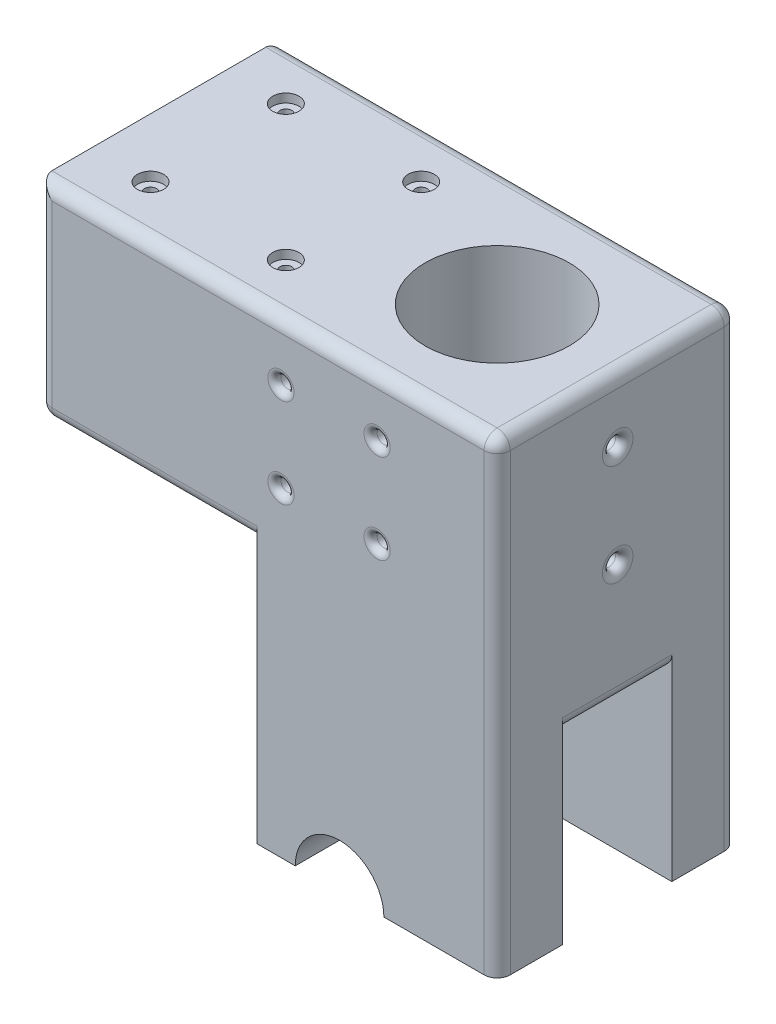
SolidWorks part; units mm, degrees
ref_plane "Front Plane" through (0, 0, 0) normal (1, 0, 0) x (0, 1, 0)
ref_plane "Top Plane" through (0, 0, 0) normal (0, 0, 1) x (0, 1, 0)
ref_plane "Right Plane" through (0, 0, 0) normal (0, 1, 0) x (-1, 0, 0)
sketch "Sketch1" plane through (0, 0, 0) normal (0, 0, 1) x (0, 1, 0)
  line L1 (-32.5, 27.5) -> (32.5, 27.5)
  line L2 (-32.5, 27.5) -> (-32.5, -27.5)
  line L3 (-32.5, -27.5) -> (32.5, -27.5)
  line L4 (32.5, 27.5) -> (32.5, -27.5)
  line L5 (-32.5, 27.5) -> (32.5, -27.5) construction
  line L6 (-32.5, -27.5) -> (32.5, 27.5) construction
  point P0 (0, 0)
  dimension "D1" = 65
  dimension "D2" = 55
extrude "Boss-Extrude1" add sketch "Sketch1" along normal blind 55
sketch "Sketch2" plane through (0, 32.5, 0) normal (0, 1, 0) x (-1, 0, 0)
  line L0 (-27.5, 55) -> (27.5, 0) construction
  line L1 (-27.5, 0) -> (27.5, 55) construction
  circle A0 centre (0, 27.5) radius 16.5
  point P15 (0, 27.5)
  dimension "D1" = 33
extrude "Cut-Extrude1" cut sketch "Sketch2" against normal blind 55
sketch "Sketch3" plane through (-27.5, 0, 0) normal (-1, 0, 0) x (0, -1, 0)
  line L0 (-32.5, 0) -> (32.5, 0) construction
  line L1 (-32.5, 55) -> (14.5, 55)
  line L2 (-32.5, 55) -> (-32.5, 0)
  line L3 (-32.5, 0) -> (14.5, 0)
  line L4 (14.5, 55) -> (14.5, 0)
  dimension "D1" = 47
extrude "Boss-Extrude2" add sketch "Sketch3" along normal blind 50
sketch "Sketch5" plane through (0, -14.5, 0) normal (0, -1, 0) x (1, 0, 0)
  line L0 (-77.5, 55) -> (-27.5, 55) construction
  line L1 (-69.7, 48.6) -> (-27.5, 48.6)
  line L2 (-69.7, 48.6) -> (-69.7, 6.4)
  line L3 (-69.7, 6.4) -> (-27.5, 6.4)
  line L4 (-27.5, 48.6) -> (-27.5, 6.4)
  line L5 (-77.5, 0) -> (-27.5, 0) construction
  line L7 (-27.5, 0) -> (-27.5, 55) construction
  dimension "D1" = 42.2
  dimension "D2" = 42.2
  dimension "D3" = 6.4
  dimension "D4" = 6.4
extrude "Cut-Extrude2" cut sketch "Sketch5" against normal blind 42
sketch "Sketch6" plane through (0, -14.5, 0) normal (0, -1, 0) x (1, 0, 0)
  line L0 (-77.5, 0) -> (-77.5, 55) construction
  line L1 (-77.5, 37.1) -> (-69.7, 37.1)
  line L2 (-77.5, 37.1) -> (-77.5, 17.9)
  line L3 (-77.5, 17.9) -> (-69.7, 17.9)
  line L4 (-69.7, 37.1) -> (-69.7, 17.9)
  line L5 (-69.7, 48.6) -> (-69.7, 6.4) construction
  line L6 (-27.5, 48.6) -> (-69.7, 48.6) construction
  line L7 (-69.7, 6.4) -> (-27.5, 6.4) construction
  dimension "D1" = 11.5
  dimension "D2" = 11.5
extrude "Cut-Extrude3" cut sketch "Sketch6" against normal blind 42
fillet "Fillet2" radius 3 2 edges at (-77.5, -14.5, 46.05) (-77.5, -14.5, 8.95)
sketch "Sketch7" plane through (0, -32.5, 0) normal (0, -1, 0) x (1, 0, 0)
  line L0 (27.5, 55) -> (27.5, 0) construction
  line L1 (-27.5, 55) -> (27.5, 55)
  line L2 (-27.5, 55) -> (-27.5, 40)
  line L3 (-27.5, 40) -> (27.5, 40)
  line L4 (27.5, 55) -> (27.5, 40)
  line L6 (-27.5, 0) -> (27.5, 0)
  line L7 (-27.5, 0) -> (-27.5, 15)
  line L8 (-27.5, 15) -> (27.5, 15)
  line L9 (27.5, 0) -> (27.5, 15)
  dimension "D1" = 15
  dimension "D2" = 15
extrude "Boss-Extrude3" add sketch "Sketch7" along normal blind 42
sketch "Sketch9" plane through (0, 0, 48.6) normal (0, 0, -1) x (1, 0, 0)
  line L0 (-27.5, 14.5) -> (-69.7, 14.5) construction
  line L1 (-48.6, 14.5) -> (-48.6, 74.5) construction
  line L2 (-48.6, 74.5) -> (-8.6, 74.5) construction
  line L3 (-8.6, 74.5) -> (-8.6, 34.5) construction
  circle A0 centre (-8.6, 74.5) radius 40 construction
  circle A1 centre (-8.6, 74.5) radius 10.15
  dimension "D4" = 20.3
  dimension "D1" = 40
  dimension "D2" = 40
  dimension "D3" = 60
extrude "Cut-Extrude4" cut sketch "Sketch9" against normal through all and the other way through all
sketch "Sketch10" plane through (0, -74.5, 0) normal (0, -1, 0) x (1, 0, 0)
  line L0 (-18.75, 55) -> (-18.75, 40) construction
  line L1 (-27.5, 55) -> (-18.75, 55) construction
  line L2 (-27.5, 55) -> (-27.5, 40) construction
  line L3 (-27.5, 40) -> (-18.75, 40) construction
  line L4 (-18.75, 55) -> (-18.75, 40) construction
  line L5 (-27.5, 47.5) -> (-18.75, 55) construction
  line L6 (1.55, 55) -> (27.5, 55) construction
  line L7 (1.55, 55) -> (1.55, 40) construction
  line L8 (1.55, 40) -> (27.5, 40) construction
  line L9 (27.5, 55) -> (27.5, 40) construction
  line L10 (-27.5, 15) -> (-18.75, 15) construction
  line L11 (-27.5, 15) -> (-27.5, 0) construction
  line L12 (-27.5, 0) -> (-18.75, 0) construction
  line L13 (-18.75, 15) -> (-18.75, 0) construction
  line L14 (1.55, 15) -> (27.5, 15) construction
  line L15 (1.55, 15) -> (1.55, 0) construction
  line L16 (1.55, 0) -> (27.5, 0) construction
  line L17 (27.5, 15) -> (27.5, 0) construction
  line L18 (-27.5, 55) -> (-18.75, 47.5) construction
  line L19 (-18.75, 47.5) -> (-27.5, 40) construction
  line L20 (-27.5, 47.5) -> (-18.75, 40) construction
  line L21 (1.55, 55) -> (14.525, 40) construction
  line L22 (14.525, 40) -> (27.5, 55) construction
  line L23 (1.55, 40) -> (14.525, 55) construction
  line L24 (14.525, 55) -> (27.5, 40) construction
  line L25 (-27.5, 0) -> (-18.75, 7.5) construction
  line L26 (-18.75, 7.5) -> (-27.5, 15) construction
  line L27 (-18.75, 0) -> (-27.5, 7.5) construction
  line L28 (-27.5, 7.5) -> (-18.75, 15) construction
  line L29 (1.55, 0) -> (14.525, 15) construction
  line L30 (14.525, 15) -> (27.5, 0) construction
  line L31 (27.5, 15) -> (14.525, 0) construction
  line L32 (14.525, 0) -> (1.55, 15) construction
  circle A0 centre (-23.125, 51.25) radius 1.5
  circle A1 centre (-23.125, 43.75) radius 1.5
  circle A2 centre (8.0375, 47.5) radius 1.5
  circle A3 centre (21.0125, 47.5) radius 1.5
  circle A4 centre (-23.125, 11.25) radius 1.5
  circle A5 centre (-23.125, 3.75) radius 1.5
  circle A6 centre (8.0375, 7.5) radius 1.5
  circle A7 centre (21.0125, 7.5) radius 1.5
  dimension "D1" = 3
extrude "Cut-Extrude5" cut sketch "Sketch10" against normal blind 20
fillet "Fillet4" radius 1.5 8 edges at (21.0125, -74.5, 46) (8.0375, -74.5, 46) (-23.125, -74.5, 42.25) (-23.125, -74.5, 49.75) (21.0125, -74.5, 6) (8.0375, -74.5, 6) (-23.125, -74.5, 2.25) (-23.125, -74.5, 9.75)
fillet "Fillet5" radius 3 13 edges at (-77.5, 10.5, 55) (-76.6213, -13.6213, 55) (-77.5, 10.5, 0) (-76.6213, -13.6213, 0) (-27.5, -32.5, 27.5) (-51, -14.5, 55) (-51, -14.5, 0) (27.5, -32.5, 27.5) (27.5, -21, 0) (27.5, -21, 55) (27.5, 32.5, 27.5) (-25, 32.5, 55) (-25, 32.5, 0)
sketch "Sketch12" plane through (0, 32.5, 0) normal (0, 1, 0) x (1, 0, 0)
  circle A0 centre (-33, -42.9) radius 1.35
  circle A1 centre (-33, -11.9) radius 1.35
  circle A2 centre (-64, -42.9) radius 1.35
  circle A3 centre (-64, -11.9) radius 1.35
  dimension "D1" = 2.7
extrude "Cut-Extrude6" cut sketch "Sketch12" against normal blind 10
sketch "Sketch13" plane through (0, 32.5, 0) normal (0, 1, 0) x (1, 0, 0)
  circle A0 centre (-33, -42.9) radius 3
  circle A1 centre (-64, -42.9) radius 3
  circle A2 centre (-33, -11.9) radius 3
  circle A3 centre (-64, -11.9) radius 3
extrude "Cut-Extrude7" cut sketch "Sketch13" against normal blind 2
sketch "Sketch15" plane through (0, -74.5, 0) normal (0, -1, 0) x (1, 0, 0)
  line L5 (1.55, 15) -> (1.55, 0) construction
  line L6 (-18.75, 0) -> (1.55, 0)
  line L7 (-18.75, 0) -> (-18.75, 3.5)
  line L8 (-18.75, 3.5) -> (1.55, 3.5)
  line L9 (1.55, 0) -> (1.55, 3.5)
  dimension "D2" = 3.5
extrude "Boss-Extrude4" add sketch "Sketch15" against normal blind 12
sketch "Sketch16" plane through (27.5, 0, 0) normal (1, 0, 0) x (0, 1, 0)
  line L0 (32.5, 27.5) -> (-29.5, 27.5) construction
  line L1 (32.5, 52) -> (32.5, 3) construction
  line L2 (-29.5, 40) -> (-29.5, 15) construction
  line L3 (-5.4, 13.2284) -> (-5.4, 41.5716) construction
  circle A0 centre (-5.4, 27.4) radius 1.5
  circle A1 centre (17.9, 27.4) radius 1.5
  dimension "D1" = 3
extrude "Cut-Extrude8" cut sketch "Sketch16" against normal blind 15
fillet "Fillet6" radius 2 2 edges at (27.5, -5.4, 25.9) (27.5, 17.9, 25.9)
sketch "Sketch17" plane through (0, 0, 55) normal (0, 0, 1) x (1, 0, 0)
  line L0 (16.5406, 29.5) -> (-16.5359, 29.5) construction
  line L1 (24.5, 29.5) -> (-74.5, 29.5) construction
  line L2 (0.0024, 29.5) -> (0.0024, -11.5) construction
  line L3 (-27.5, -11.5) -> (10.3, -11.5) construction
  line L4 (-8.6, 29.5) -> (-8.6, -11.5) construction
  line L5 (-16.5359, 29.5) -> (-27.5, 29.5) construction
  line L6 (-8.6, 29.5) -> (0.0024, 9) construction
  line L7 (0.0024, 9) -> (-8.6, -11.5) construction
  line L8 (-22.0179, 29.5) -> (-22.0179, -11.5) construction
  line L12 (0.0024, -11.5) -> (-8.6, 9) construction
  line L13 (-8.6, 9) -> (0.0024, 29.5) construction
  circle A0 centre (0.0024, 19.25) radius 1.5
  circle A1 centre (0.0024, -1.25) radius 1.5
  circle A2 centre (-22.0179, 19.25) radius 1.5
  circle A3 centre (-22.0179, -1.25) radius 1.5
  dimension "D1" = 3
extrude "Cut-Extrude10" cut sketch "Sketch17" against normal blind 15
fillet "Fillet7" radius 1.5 4 edges at (1.5024, 19.25, 55) (1.5024, -1.25, 55) (-20.5179, -1.25, 55) (-20.5179, 19.25, 55)
